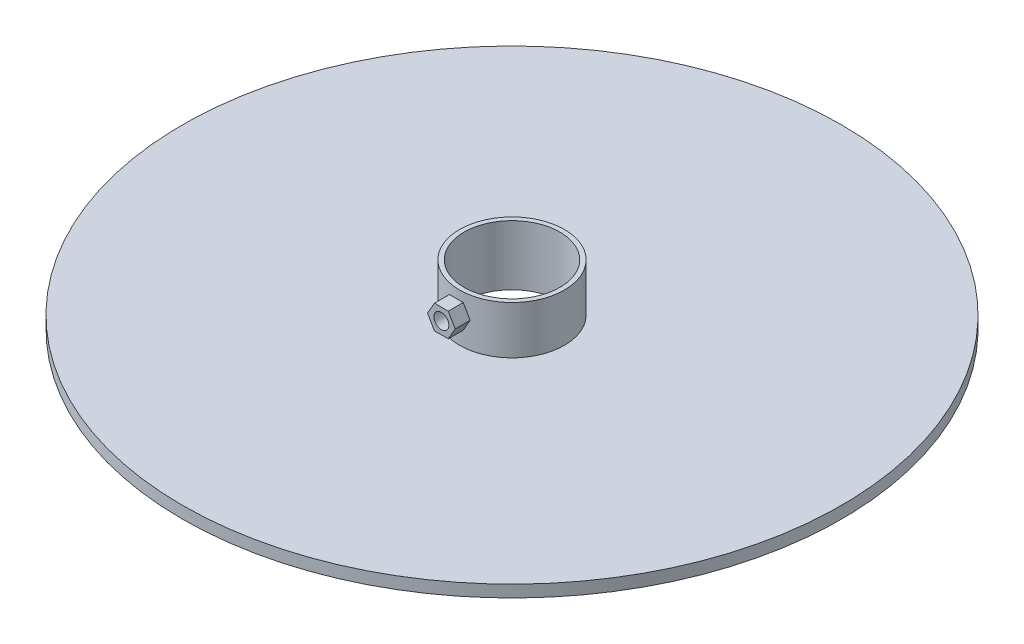
SolidWorks part; units mm, degrees
other "DetailItem2"
other "Weld Folder"
other "Weld Bead1"
ref_plane "Front Plane" through (0, 0, 0) normal (0, 0, 1) x (1, 0, 0)
ref_plane "Top Plane" through (0, 0, 0) normal (0, 1, 0) x (1, 0, 0)
ref_plane "Right Plane" through (0, 0, 0) normal (1, 0, 0) x (0, 0, -1)
sketch "Sketch1" plane through (0, 0, 0) normal (1, 0, 0) x (0, 0, -1)
  line L4 (0, 0) -> (0, -93.7757) construction
  line L5 (17.5, -625.5029) -> (17.5, -609.5029)
  line L6 (17.5, -609.5029) -> (16, -609.5029)
  line L7 (16, -609.5029) -> (16, -629.5029)
  line L8 (16, -629.5029) -> (110, -629.5029)
  line L9 (110, -629.5029) -> (110, -625.5029)
  line L10 (110, -625.5029) -> (17.5, -625.5029)
  line L11 (26, -629.5029) -> (-26, -629.5029) construction
  dimension "D1" = 4
  dimension "D2" = 1.5
  dimension "D3" = 35
  dimension "D4" = 20
  dimension "D5" = 220
revolve "Revolve1" add sketch "Sketch1" angle 360 about L4
ref_plane "Plane1" through (0, 0, 17.5) normal (0, 0, 1) x (1, 0, 0)
sketch "Sketch3" plane through (0, 0, 17.5) normal (0, 0, 1) x (1, 0, 0)
  line L0 (17.5, -609.5029) -> (-17.5, -609.5029) construction
  circle A0 centre (-1.0822, -616.5029) radius 3
  dimension "D1" = 6
  dimension "D2" = 7
extrude "Cut-Extrude1" cut sketch "Sketch3" against normal up to next
sketch "Sketch4" plane through (0, 0, 17.5) normal (0, 0, 1) x (1, 0, 0)
  line L1 (3.5366, -616.5029) -> (1.2272, -612.5029)
  line L2 (1.2272, -612.5029) -> (-3.3916, -612.5029)
  line L3 (-3.3916, -612.5029) -> (-5.701, -616.5029)
  line L4 (-5.701, -616.5029) -> (-3.3916, -620.5029)
  line L5 (-3.3916, -620.5029) -> (1.2272, -620.5029)
  line L6 (1.2272, -620.5029) -> (3.5366, -616.5029)
  circle A0 centre (-1.0822, -616.5029) radius 4 construction
  circle A1 centre (-1.0822, -616.5029) radius 2.5
  dimension "D2" = 5
  dimension "D1" = 8
extrude "Boss-Extrude1" add sketch "Sketch4" along normal blind 5
